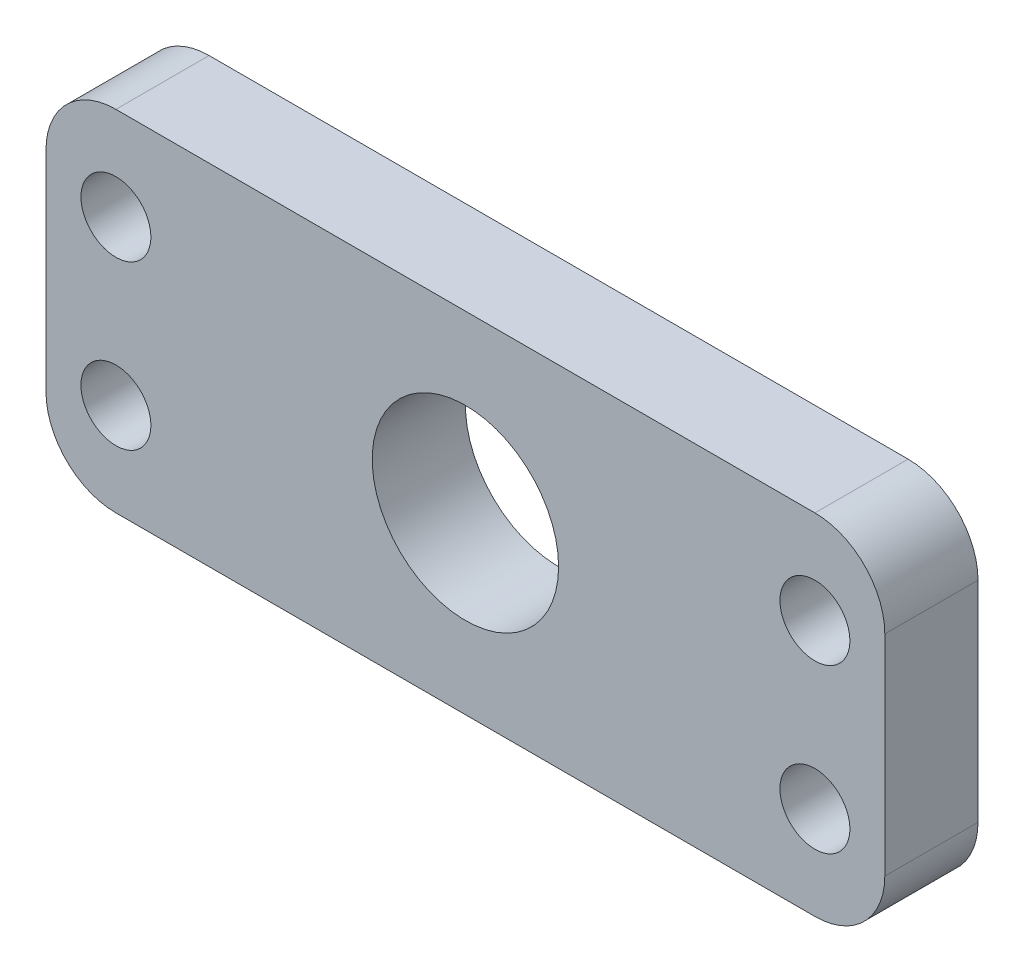
SolidWorks part; units mm, degrees
material "Thornel Mat VMA"
ref_plane "前视基准面" through (0, 0, 0) normal (0, 0, 1) x (1, 0, 0)
ref_plane "上视基准面" through (0, 0, 0) normal (0, 1, 0) x (1, 0, 0)
ref_plane "右视基准面" through (0, 0, 0) normal (1, 0, 0) x (0, 0, -1)
sketch "草图1" plane through (0, 0, 0) normal (0, 0, 1) x (1, 0, 0)
  line L0 (-25, 0) -> (18, 0) construction
  line L1 (-18, 7.5) -> (18, 7.5)
  line L2 (-18, -7.5) -> (18, -7.5)
  line L3 (-18, -7.5) -> (-18, 7.5)
  line L4 (18, -7.5) -> (18, 7.5)
  line L5 (0, -7.5) -> (0, 0) construction
  point P3 (0, 0)
  point P9 (18, 0)
  dimension "D3" = 36
  dimension "D1" = 15
extrude "凸台-拉伸1" add sketch "草图1" along normal blind 4
sketch "草图2" plane through (0, 0, 4) normal (0, 0, 1) x (1, 0, 0)
  circle A0 centre (0, 0) radius 4
  dimension "D1" = 8
extrude "切除-拉伸1" cut sketch "草图2" against normal through all
sketch "草图4" plane through (0, 0, 0) normal (0, 0, -1) x (-1, 0, 0)
  line L1 (15, -3.5) -> (-15, -3.5) construction
  line L2 (15, -3.5) -> (15, 3.5) construction
  line L3 (15, 3.5) -> (-15, 3.5) construction
  line L4 (-15, -3.5) -> (-15, 3.5) construction
  line L5 (15, -3.5) -> (-15, 3.5) construction
  line L6 (15, 3.5) -> (-15, -3.5) construction
  circle A0 centre (15, -3.5) radius 1.5
  circle A1 centre (15, 3.5) radius 1.5
  circle A2 centre (-15, 3.5) radius 1.5
  circle A3 centre (-15, -3.5) radius 1.5
  point P0 (0, 0)
  dimension "D3" = 3
  dimension "D1" = 30
  dimension "D2" = 7
extrude "切除-拉伸2" cut sketch "草图4" against normal through all
fillet "圆角1" radius 3 4 edges at (18, -7.5, 2) (18, 7.5, 2) (-18, -7.5, 2) (-18, 7.5, 2)
